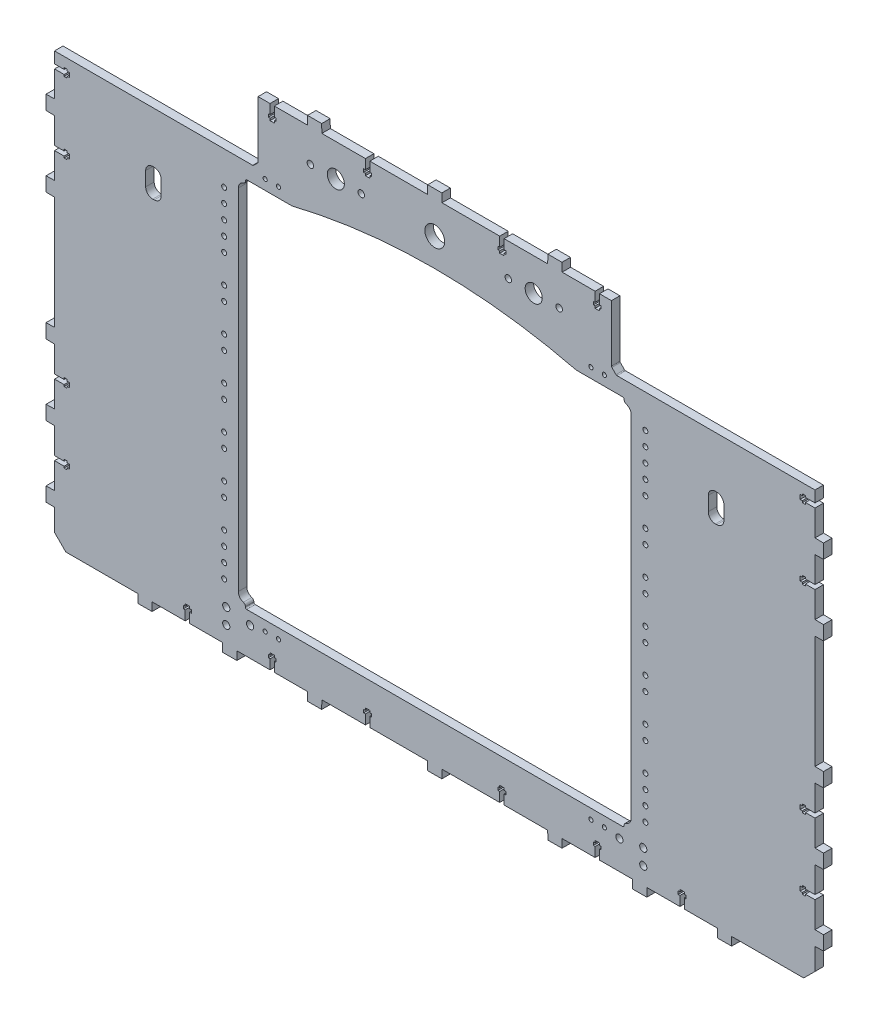
SolidWorks part; units mm, degrees
material "Клен"
ref_plane "Front" through (0, 0, 0) normal (0, 0, 1) x (1, 0, 0)
ref_plane "Top" through (0, 0, 0) normal (0, 1, 0) x (1, 0, 0)
ref_plane "Right" through (0, 0, 0) normal (1, 0, 0) x (0, 0, -1)
sketch "Эскиз1" plane through (0, 0, 0) normal (0, 0, 1) x (1, 0, 0)
  line L6 (1560.5805, 76.7865) -> (1826.5797, 76.7865)
  line L7 (1827.5797, 78.0783) -> (1827.5797, 77.7865)
  line L8 (1832.5805, 332.0072) -> (1832.5797, 84.7865)
  line L9 (1827.5805, 339.0072) -> (1827.5805, 338.7154)
  line L10 (1826.5805, 340.0072) -> (1793.6805, 340.0072)
  line L11 (1560.5805, 340.0072) -> (1592.5638, 340.0072)
  line L13 (1559.5805, 339.0072) -> (1559.5805, 338.7154)
  line L15 (1554.5805, 84.7865) -> (1554.5805, 332.0072)
  line L17 (1559.5805, 78.0783) -> (1559.5805, 77.7865)
  line L18 (1524.5805, 401.0072) -> (1524.5805, 24.1014) construction
  line L19 (1862.5805, 416.6106) -> (1862.5805, 5.7676) construction
  line L20 (1424.5805, 401.0072) -> (1424.5805, 24.1014) construction
  line L21 (1962.5805, 416.6106) -> (1962.5805, 5.7676) construction
  line L22 (1433.5805, 343.0572) -> (1435.0805, 343.0572)
  line L23 (1433.5805, 289.9572) -> (1433.5805, 288.7572)
  line L24 (1433.5805, 149.9572) -> (1433.5805, 148.7572)
  line L25 (1424.5805, 121.4072) -> (1424.5805, 103.0572)
  line L26 (1431.3805, 293.0572) -> (1431.3805, 294.2572)
  line L27 (1431.3805, 154.2572) -> (1433.5805, 154.2572)
  line L28 (1418.5805, 71.5072) -> (1424.5805, 71.4072)
  line L29 (1418.5805, 321.5072) -> (1418.5805, 311.5072)
  line L30 (1418.5805, 311.5072) -> (1424.5805, 311.4072)
  line L31 (1424.5805, 149.9572) -> (1424.5805, 131.6072)
  line L32 (1418.5805, 81.5072) -> (1418.5805, 71.5072)
  line L33 (1433.5805, 338.7572) -> (1431.3805, 338.7572)
  line L34 (1424.5805, 293.0572) -> (1431.3805, 293.0572)
  line L35 (1424.5805, 153.0572) -> (1431.3805, 153.0572)
  line L36 (1433.5805, 103.0572) -> (1435.0805, 103.0572)
  line L37 (1424.5805, 99.9572) -> (1424.5805, 81.6072)
  line L38 (1424.5805, 321.6072) -> (1418.5805, 321.5072)
  line L39 (1433.5805, 293.0572) -> (1435.0805, 293.0572)
  line L40 (1433.5805, 148.7572) -> (1431.3805, 148.7572)
  line L41 (1435.0805, 343.0572) -> (1435.0805, 339.9572)
  line L42 (1431.3805, 289.9572) -> (1424.5805, 289.9572)
  line L43 (1424.5805, 181.6072) -> (1418.5805, 181.5072)
  line L44 (1431.3805, 103.0572) -> (1431.3805, 104.2572)
  line L45 (1435.0805, 103.0572) -> (1435.0805, 99.9572)
  line L46 (1431.3805, 343.0572) -> (1431.3805, 344.2572)
  line L47 (1424.5805, 261.4072) -> (1424.5805, 181.6072)
  line L48 (1433.5805, 153.0572) -> (1435.0805, 153.0572)
  line L49 (1424.5805, 103.0572) -> (1431.3805, 103.0572)
  line L50 (1433.5805, 104.2572) -> (1433.5805, 103.0572)
  line L51 (1424.5805, 311.4072) -> (1424.5805, 293.0572)
  line L52 (1433.5805, 294.2572) -> (1433.5805, 293.0572)
  line L53 (1424.5805, 131.6072) -> (1418.5805, 131.5072)
  line L54 (1431.3805, 338.7572) -> (1431.3805, 339.9572)
  line L55 (1418.5805, 271.5072) -> (1418.5805, 261.5072)
  line L56 (1433.5805, 154.2572) -> (1433.5805, 153.0572)
  line L57 (1433.5805, 98.7572) -> (1431.3805, 98.7572)
  line L58 (1424.5805, 81.6072) -> (1418.5805, 81.5072)
  line L59 (1424.5805, 343.0572) -> (1431.3805, 343.0572)
  line L60 (1431.3805, 339.9572) -> (1424.5805, 339.9572)
  line L61 (1435.0805, 289.9572) -> (1433.5805, 289.9572)
  line L62 (1431.3805, 148.7572) -> (1431.3805, 149.9572)
  line L63 (1435.0805, 339.9572) -> (1433.5805, 339.9572)
  line L64 (1431.3805, 294.2572) -> (1433.5805, 294.2572)
  line L65 (1424.5805, 289.9572) -> (1424.5805, 271.6072)
  line L66 (1433.5805, 99.9572) -> (1433.5805, 98.7572)
  line L67 (1431.3805, 98.7572) -> (1431.3805, 99.9572)
  line L68 (1433.5805, 344.2572) -> (1433.5805, 343.0572)
  line L69 (1424.5805, 271.6072) -> (1418.5805, 271.5072)
  line L70 (1435.0805, 153.0572) -> (1435.0805, 149.9572)
  line L71 (1424.5805, 71.4072) -> (1424.5805, 56.0072)
  line L72 (1431.3805, 344.2572) -> (1433.5805, 344.2572)
  line L73 (1435.0805, 293.0572) -> (1435.0805, 289.9572)
  line L74 (1433.5805, 288.7572) -> (1431.3805, 288.7572)
  line L75 (1418.5805, 131.5072) -> (1418.5805, 121.5072)
  line L76 (1435.0805, 99.9572) -> (1433.5805, 99.9572)
  line L77 (1424.5805, 351.0072) -> (1424.5805, 343.0572)
  line L78 (1418.5805, 171.5072) -> (1424.5805, 171.4072)
  line L79 (1418.5805, 121.5072) -> (1424.5805, 121.4072)
  line L80 (1431.3805, 104.2572) -> (1433.5805, 104.2572)
  line L81 (1431.3805, 288.7572) -> (1431.3805, 289.9572)
  line L82 (1424.5805, 171.4072) -> (1424.5805, 153.0572)
  line L83 (1431.3805, 149.9572) -> (1424.5805, 149.9572)
  line L84 (1433.5805, 339.9572) -> (1433.5805, 338.7572)
  line L85 (1418.5805, 261.5072) -> (1424.5805, 261.4072)
  line L86 (1418.5805, 181.5072) -> (1418.5805, 171.5072)
  line L87 (1431.3805, 99.9572) -> (1424.5805, 99.9572)
  line L88 (1424.5805, 339.9572) -> (1424.5805, 321.6072)
  line L89 (1431.3805, 153.0572) -> (1431.3805, 154.2572)
  line L90 (1435.0805, 149.9572) -> (1433.5805, 149.9572)
  line L91 (1424.5805, 56.0072) -> (1432.5805, 48.0072)
  line L92 (1424.5805, 351.0072) -> (1524.5805, 351.0072)
  line L93 (1432.5805, 48.0072) -> (1483.4805, 48.0072)
  line L94 (1953.5805, 99.9572) -> (1952.0805, 99.9572)
  line L95 (1955.7805, 154.2572) -> (1955.7805, 153.0572)
  line L96 (1953.5805, 289.9572) -> (1952.0805, 289.9572)
  line L97 (1953.5805, 343.0572) -> (1953.5805, 344.2572)
  line L98 (1962.5805, 99.9572) -> (1955.7805, 99.9572)
  line L99 (1955.7805, 153.0572) -> (1962.5805, 153.0572)
  line L100 (1953.5805, 294.2572) -> (1955.7805, 294.2572)
  line L101 (1955.7805, 338.7572) -> (1953.5805, 338.7572)
  line L102 (1953.5805, 103.0572) -> (1953.5805, 104.2572)
  line L103 (1952.0805, 153.0572) -> (1953.5805, 153.0572)
  line L104 (1955.7805, 288.7572) -> (1953.5805, 288.7572)
  line L105 (1962.5805, 321.6072) -> (1962.5805, 339.9572)
  line L106 (1955.7805, 344.2572) -> (1955.7805, 343.0572)
  line L107 (1968.5805, 131.5072) -> (1962.5805, 131.6072)
  line L108 (1962.5805, 149.9572) -> (1955.7805, 149.9572)
  line L109 (1968.5805, 261.5072) -> (1968.5805, 271.5072)
  line L110 (1962.5805, 289.9572) -> (1955.7805, 289.9572)
  line L111 (1955.7805, 343.0572) -> (1962.5805, 343.0572)
  line L112 (1952.0805, 99.9572) -> (1952.0805, 103.0572)
  line L113 (1955.7805, 149.9572) -> (1955.7805, 148.7572)
  line L114 (1952.0805, 293.0572) -> (1953.5805, 293.0572)
  line L115 (1953.5805, 339.9572) -> (1952.0805, 339.9572)
  line L116 (1962.5805, 56.0072) -> (1962.5805, 71.4072)
  line L117 (1955.7805, 103.0572) -> (1962.5805, 103.0572)
  line L118 (1968.5805, 181.5072) -> (1962.5805, 181.6072)
  line L119 (1955.7805, 293.0572) -> (1962.5805, 293.0572)
  line L120 (1953.5805, 344.2572) -> (1955.7805, 344.2572)
  line L121 (1962.5805, 71.4072) -> (1968.5805, 71.5072)
  line L122 (1962.5805, 131.6072) -> (1962.5805, 149.9572)
  line L123 (1968.5805, 171.5072) -> (1968.5805, 181.5072)
  line L124 (1968.5805, 271.5072) -> (1962.5805, 271.6072)
  line L125 (1953.5805, 104.2572) -> (1955.7805, 104.2572)
  line L126 (1953.5805, 153.0572) -> (1953.5805, 154.2572)
  line L127 (1953.5805, 293.0572) -> (1953.5805, 294.2572)
  line L128 (1953.5805, 98.7572) -> (1953.5805, 99.9572)
  line L129 (1962.5805, 121.4072) -> (1968.5805, 121.5072)
  line L130 (1962.5805, 261.4072) -> (1968.5805, 261.5072)
  line L131 (1952.0805, 289.9572) -> (1952.0805, 293.0572)
  line L132 (1952.0805, 343.0572) -> (1953.5805, 343.0572)
  line L133 (1968.5805, 81.5072) -> (1962.5805, 81.6072)
  line L134 (1955.7805, 148.7572) -> (1953.5805, 148.7572)
  line L135 (1962.5805, 293.0572) -> (1962.5805, 311.4072)
  line L136 (1952.0805, 339.9572) -> (1952.0805, 343.0572)
  line L137 (1955.7805, 98.7572) -> (1953.5805, 98.7572)
  line L138 (1962.5805, 103.0572) -> (1962.5805, 121.4072)
  line L139 (1962.5805, 181.6072) -> (1962.5805, 261.4072)
  line L140 (1962.5805, 311.4072) -> (1968.5805, 311.5072)
  line L141 (1952.0805, 103.0572) -> (1953.5805, 103.0572)
  line L142 (1955.7805, 294.2572) -> (1955.7805, 293.0572)
  line L143 (1962.5805, 339.9572) -> (1955.7805, 339.9572)
  line L144 (1955.7805, 104.2572) -> (1955.7805, 103.0572)
  line L145 (1953.5805, 154.2572) -> (1955.7805, 154.2572)
  line L146 (1955.7805, 289.9572) -> (1955.7805, 288.7572)
  line L147 (1968.5805, 121.5072) -> (1968.5805, 131.5072)
  line L148 (1953.5805, 288.7572) -> (1953.5805, 289.9572)
  line L149 (1955.7805, 339.9572) -> (1955.7805, 338.7572)
  line L150 (1954.5805, 48.0072) -> (1962.5805, 56.0072)
  line L151 (1962.5805, 81.6072) -> (1962.5805, 99.9572)
  line L152 (1953.5805, 149.9572) -> (1952.0805, 149.9572)
  line L153 (1962.5805, 171.4072) -> (1968.5805, 171.5072)
  line L154 (1968.5805, 311.5072) -> (1968.5805, 321.5072)
  line L155 (1955.7805, 99.9572) -> (1955.7805, 98.7572)
  line L156 (1952.0805, 149.9572) -> (1952.0805, 153.0572)
  line L157 (1962.5805, 271.6072) -> (1962.5805, 289.9572)
  line L158 (1968.5805, 321.5072) -> (1962.5805, 321.6072)
  line L159 (1962.5805, 343.0572) -> (1962.5805, 351.0072)
  line L160 (1968.5805, 71.5072) -> (1968.5805, 81.5072)
  line L161 (1953.5805, 148.7572) -> (1953.5805, 149.9572)
  line L162 (1962.5805, 153.0572) -> (1962.5805, 171.4072)
  line L163 (1953.5805, 338.7572) -> (1953.5805, 339.9572)
  line L164 (1862.5805, 351.0072) -> (1962.5805, 351.0072)
  line L165 (1954.5805, 48.0072) -> (1903.6805, 48.0072)
  line L166 (1325.5433, 339.9572) -> (1983.9894, 339.9572) construction
  line L167 (1983.9894, 304.9572) -> (1788.8393, 304.9572) construction
  line L168 (1892.5805, 416.6106) -> (1892.5805, 273.8352) construction
  line L169 (1693.5805, 412.8647) -> (1693.5805, 297.5072) construction
  line L170 (1892.0805, 314.9572) -> (1893.0805, 314.9572)
  line L171 (1887.0805, 309.9572) -> (1887.0805, 299.9572)
  line L172 (1892.0805, 294.9572) -> (1893.0805, 294.9572)
  line L173 (1898.0805, 309.9572) -> (1898.0805, 299.9572)
  line L174 (1887.0805, 314.9572) -> (1898.0805, 294.9572) construction
  line L175 (1887.0805, 294.9572) -> (1898.0805, 314.9572) construction
  line L176 (1495.0805, 294.9572) -> (1494.0805, 294.9572)
  line L177 (1489.0805, 309.9572) -> (1489.0805, 299.9572)
  line L178 (1495.0805, 314.9572) -> (1494.0805, 314.9572)
  line L179 (1500.0805, 309.9572) -> (1500.0805, 299.9572)
  line L180 (1893.4805, 48.0072) -> (1893.5805, 42.0072)
  line L181 (1867.0305, 58.5072) -> (1870.1305, 58.5072)
  line L182 (1903.5805, 42.0072) -> (1903.6805, 48.0072)
  line L183 (1867.0305, 54.8072) -> (1865.8305, 54.8072)
  line L184 (1870.1305, 58.5072) -> (1870.1305, 57.0072)
  line L185 (1871.3305, 54.8072) -> (1870.1305, 54.8072)
  line L186 (1865.8305, 57.0072) -> (1867.0305, 57.0072)
  line L187 (1871.3305, 57.0072) -> (1871.3305, 54.8072)
  line L188 (1867.0305, 48.0072) -> (1867.0305, 54.8072)
  line L189 (1870.1305, 57.0072) -> (1871.3305, 57.0072)
  line L190 (1870.1305, 54.8072) -> (1870.1305, 48.0072)
  line L192 (1865.8305, 54.8072) -> (1865.8305, 57.0072)
  line L193 (1893.5805, 42.0072) -> (1903.5805, 42.0072)
  line L194 (1867.0305, 57.0072) -> (1867.0305, 58.5072)
  line L195 (1867.0305, 48.0072) -> (1854.5805, 48.0072)
  line L196 (1893.4805, 48.0072) -> (1870.1305, 48.0072)
  line L197 (1493.5805, 42.0072) -> (1493.6805, 48.0072)
  line L198 (1521.3305, 57.0072) -> (1521.3305, 54.8072)
  line L199 (1517.0305, 48.0072) -> (1517.0305, 54.8072)
  line L200 (1483.5805, 42.0072) -> (1493.5805, 42.0072)
  line L201 (1515.8305, 57.0072) -> (1517.0305, 57.0072)
  line L202 (1521.3305, 54.8072) -> (1520.1305, 54.8072)
  line L203 (1483.4805, 48.0072) -> (1483.5805, 42.0072)
  line L204 (1517.0305, 57.0072) -> (1517.0305, 58.5072)
  line L205 (1517.0305, 58.5072) -> (1520.1305, 58.5072)
  line L206 (1517.0305, 54.8072) -> (1515.8305, 54.8072)
  line L207 (1520.1305, 54.8072) -> (1520.1305, 48.0072)
  line L209 (1520.1305, 58.5072) -> (1520.1305, 57.0072)
  line L210 (1520.1305, 57.0072) -> (1521.3305, 57.0072)
  line L211 (1515.8305, 54.8072) -> (1515.8305, 57.0072)
  line L212 (1520.1305, 48.0072) -> (1532.5805, 48.0072)
  line L213 (1493.6805, 48.0072) -> (1517.0305, 48.0072)
  line L552 (1568.2876, 354.2143) -> (1565.3733, 351.3001)
  line L553 (1564.6662, 351.0072) -> (1524.5805, 351.0072)
  line L624 (1532.5805, 48.0072) -> (1543.4805, 48.0072)
  line L625 (1543.4805, 48.0072) -> (1543.5805, 42.0072)
  line L626 (1543.5805, 42.0072) -> (1553.5805, 42.0072)
  line L627 (1553.5805, 42.0072) -> (1553.6805, 48.0072)
  line L628 (1553.6805, 48.0072) -> (1577.0305, 48.0072)
  line L629 (1577.0305, 48.0072) -> (1577.0305, 54.8072)
  line L630 (1577.0305, 54.8072) -> (1575.8305, 54.8072)
  line L631 (1575.8305, 54.8072) -> (1575.8305, 57.0072)
  line L632 (1575.8305, 57.0072) -> (1577.0305, 57.0072)
  line L633 (1577.0305, 57.0072) -> (1577.0305, 58.5072)
  line L634 (1577.0305, 58.5072) -> (1580.1305, 58.5072)
  line L635 (1580.1305, 58.5072) -> (1580.1305, 57.0072)
  line L636 (1580.1305, 57.0072) -> (1581.3305, 57.0072)
  line L637 (1581.3305, 57.0072) -> (1581.3305, 54.8072)
  line L638 (1581.3305, 54.8072) -> (1580.1305, 54.8072)
  line L639 (1580.1305, 54.8072) -> (1580.1305, 48.0072)
  line L640 (1580.1305, 48.0072) -> (1603.4805, 48.0072)
  line L641 (1603.4805, 48.0072) -> (1603.5805, 42.0072)
  line L642 (1603.5805, 42.0072) -> (1613.5805, 42.0072)
  line L643 (1613.5805, 42.0072) -> (1613.6805, 48.0072)
  line L644 (1613.6805, 48.0072) -> (1644.5305, 48.0072)
  line L645 (1644.5305, 48.0072) -> (1644.5305, 54.8072)
  line L646 (1644.5305, 54.8072) -> (1643.3305, 54.8072)
  line L647 (1643.3305, 54.8072) -> (1643.3305, 57.0072)
  line L648 (1643.3305, 57.0072) -> (1644.5305, 57.0072)
  line L649 (1644.5305, 57.0072) -> (1644.5305, 58.5072)
  line L650 (1644.5305, 58.5072) -> (1647.6305, 58.5072)
  line L651 (1647.6305, 58.5072) -> (1647.6305, 57.0072)
  line L652 (1647.6305, 57.0072) -> (1648.8305, 57.0072)
  line L653 (1648.8305, 57.0072) -> (1648.8305, 54.8072)
  line L654 (1648.8305, 54.8072) -> (1647.6305, 54.8072)
  line L655 (1647.6305, 54.8072) -> (1647.6305, 48.0072)
  line L656 (1647.6305, 48.0072) -> (1688.4805, 48.0072)
  line L657 (1688.4805, 48.0072) -> (1688.5805, 42.0072)
  line L658 (1688.5805, 42.0072) -> (1698.5805, 42.0072)
  line L659 (1698.5805, 42.0072) -> (1698.6805, 48.0072)
  line L660 (1698.6805, 48.0072) -> (1739.5305, 48.0072)
  line L661 (1739.5305, 48.0072) -> (1739.5305, 54.8072)
  line L662 (1739.5305, 54.8072) -> (1738.3305, 54.8072)
  line L663 (1738.3305, 54.8072) -> (1738.3305, 57.0072)
  line L664 (1738.3305, 57.0072) -> (1739.5305, 57.0072)
  line L665 (1739.5305, 57.0072) -> (1739.5305, 58.5072)
  line L666 (1739.5305, 58.5072) -> (1742.6305, 58.5072)
  line L667 (1742.6305, 58.5072) -> (1742.6305, 57.0072)
  line L668 (1742.6305, 57.0072) -> (1743.8305, 57.0072)
  line L669 (1743.8305, 57.0072) -> (1743.8305, 54.8072)
  line L670 (1743.8305, 54.8072) -> (1742.6305, 54.8072)
  line L671 (1742.6305, 54.8072) -> (1742.6305, 48.0072)
  line L672 (1742.6305, 48.0072) -> (1773.4805, 48.0072)
  line L673 (1773.4805, 48.0072) -> (1773.5805, 42.0072)
  line L674 (1773.5805, 42.0072) -> (1783.5805, 42.0072)
  line L675 (1783.5805, 42.0072) -> (1783.6805, 48.0072)
  line L676 (1783.6805, 48.0072) -> (1807.0305, 48.0072)
  line L677 (1807.0305, 48.0072) -> (1807.0305, 54.8072)
  line L678 (1807.0305, 54.8072) -> (1805.8305, 54.8072)
  line L679 (1805.8305, 54.8072) -> (1805.8305, 57.0072)
  line L680 (1805.8305, 57.0072) -> (1807.0305, 57.0072)
  line L681 (1807.0305, 57.0072) -> (1807.0305, 58.5072)
  line L682 (1807.0305, 58.5072) -> (1810.1305, 58.5072)
  line L683 (1810.1305, 58.5072) -> (1810.1305, 57.0072)
  line L684 (1810.1305, 57.0072) -> (1811.3305, 57.0072)
  line L685 (1811.3305, 57.0072) -> (1811.3305, 54.8072)
  line L686 (1811.3305, 54.8072) -> (1810.1305, 54.8072)
  line L687 (1810.1305, 54.8072) -> (1810.1305, 48.0072)
  line L688 (1810.1305, 48.0072) -> (1833.4805, 48.0072)
  line L689 (1833.4805, 48.0072) -> (1833.5805, 42.0072)
  line L690 (1833.5805, 42.0072) -> (1843.5805, 42.0072)
  line L691 (1843.5805, 42.0072) -> (1843.6805, 48.0072)
  line L692 (1843.6805, 48.0072) -> (1854.5805, 48.0072)
  line L763 (1862.5805, 351.0072) -> (1822.4947, 351.0072)
  line L764 (1821.7876, 351.3001) -> (1818.8733, 354.2143)
  line L765 (1818.5805, 354.9215) -> (1818.5805, 395.0072)
  line L766 (1818.5805, 395.0072) -> (1810.1305, 395.0072)
  line L767 (1810.1305, 395.0072) -> (1810.1305, 388.2072)
  line L768 (1810.1305, 388.2072) -> (1811.3305, 388.2072)
  line L769 (1811.3305, 388.2072) -> (1811.3305, 386.0072)
  line L770 (1811.3305, 386.0072) -> (1810.1305, 386.0072)
  line L771 (1810.1305, 386.0072) -> (1810.1305, 384.5072)
  line L772 (1810.1305, 384.5072) -> (1807.0305, 384.5072)
  line L773 (1807.0305, 384.5072) -> (1807.0305, 386.0072)
  line L774 (1807.0305, 386.0072) -> (1805.8305, 386.0072)
  line L775 (1805.8305, 386.0072) -> (1805.8305, 388.2072)
  line L776 (1805.8305, 388.2072) -> (1807.0305, 388.2072)
  line L777 (1807.0305, 388.2072) -> (1807.0305, 395.0072)
  line L778 (1807.0305, 395.0072) -> (1783.6805, 395.0072)
  line L779 (1783.6805, 395.0072) -> (1783.5805, 401.0072)
  line L780 (1783.5805, 401.0072) -> (1773.5805, 401.0072)
  line L781 (1773.5805, 401.0072) -> (1773.4805, 395.0072)
  line L782 (1773.4805, 395.0072) -> (1742.6305, 395.0072)
  line L783 (1742.6305, 395.0072) -> (1742.6305, 388.2072)
  line L784 (1742.6305, 388.2072) -> (1743.8305, 388.2072)
  line L785 (1743.8305, 388.2072) -> (1743.8305, 386.0072)
  line L786 (1743.8305, 386.0072) -> (1742.6305, 386.0072)
  line L787 (1742.6305, 386.0072) -> (1742.6305, 384.5072)
  line L788 (1742.6305, 384.5072) -> (1739.5305, 384.5072)
  line L789 (1739.5305, 384.5072) -> (1739.5305, 386.0072)
  line L790 (1739.5305, 386.0072) -> (1738.3305, 386.0072)
  line L791 (1738.3305, 386.0072) -> (1738.3305, 388.2072)
  line L792 (1738.3305, 388.2072) -> (1739.5305, 388.2072)
  line L793 (1739.5305, 388.2072) -> (1739.5305, 395.0072)
  line L794 (1739.5305, 395.0072) -> (1698.6805, 395.0072)
  line L795 (1698.6805, 395.0072) -> (1698.5805, 401.0072)
  line L796 (1698.5805, 401.0072) -> (1688.5805, 401.0072)
  line L797 (1688.5805, 401.0072) -> (1688.4805, 395.0072)
  line L798 (1688.4805, 395.0072) -> (1647.6305, 395.0072)
  line L799 (1647.6305, 395.0072) -> (1647.6305, 388.2072)
  line L800 (1647.6305, 388.2072) -> (1648.8305, 388.2072)
  line L801 (1648.8305, 388.2072) -> (1648.8305, 386.0072)
  line L802 (1648.8305, 386.0072) -> (1647.6305, 386.0072)
  line L803 (1647.6305, 386.0072) -> (1647.6305, 384.5072)
  line L804 (1647.6305, 384.5072) -> (1644.5305, 384.5072)
  line L805 (1644.5305, 384.5072) -> (1644.5305, 386.0072)
  line L806 (1644.5305, 386.0072) -> (1643.3305, 386.0072)
  line L807 (1643.3305, 386.0072) -> (1643.3305, 388.2072)
  line L808 (1643.3305, 388.2072) -> (1644.5305, 388.2072)
  line L809 (1644.5305, 388.2072) -> (1644.5305, 395.0072)
  line L810 (1644.5305, 395.0072) -> (1613.6805, 395.0072)
  line L811 (1613.6805, 395.0072) -> (1613.5805, 401.0072)
  line L812 (1613.5805, 401.0072) -> (1603.5805, 401.0072)
  line L813 (1603.5805, 401.0072) -> (1603.4805, 395.0072)
  line L814 (1603.4805, 395.0072) -> (1580.1305, 395.0072)
  line L815 (1580.1305, 395.0072) -> (1580.1305, 388.2072)
  line L816 (1580.1305, 388.2072) -> (1581.3305, 388.2072)
  line L817 (1581.3305, 388.2072) -> (1581.3305, 386.0072)
  line L818 (1581.3305, 386.0072) -> (1580.1305, 386.0072)
  line L819 (1580.1305, 386.0072) -> (1580.1305, 384.5072)
  line L820 (1580.1305, 384.5072) -> (1577.0305, 384.5072)
  line L821 (1577.0305, 384.5072) -> (1577.0305, 386.0072)
  line L822 (1577.0305, 386.0072) -> (1575.8305, 386.0072)
  line L823 (1575.8305, 386.0072) -> (1575.8305, 388.2072)
  line L824 (1575.8305, 388.2072) -> (1577.0305, 388.2072)
  line L825 (1577.0305, 388.2072) -> (1577.0305, 395.0072)
  line L826 (1577.0305, 395.0072) -> (1568.5805, 395.0072)
  line L827 (1568.5805, 395.0072) -> (1568.5805, 354.9215)
  arc A4 (1893.0805, 294.9572) -> (1898.0805, 299.9572) centre (1893.0805, 299.9572) ccw
  arc A5 (1887.0805, 299.9572) -> (1892.0805, 294.9572) centre (1892.0805, 299.9572) ccw
  arc A6 (1893.0805, 314.9572) -> (1898.0805, 309.9572) centre (1893.0805, 309.9572) cw
  arc A7 (1892.0805, 314.9572) -> (1887.0805, 309.9572) centre (1892.0805, 309.9572) ccw
  arc A8 (1568.2876, 354.2143) -> (1568.5805, 354.9215) centre (1567.5805, 354.9215) ccw
  arc A9 (1564.6662, 351.0072) -> (1565.3733, 351.3001) centre (1564.6662, 352.0072) ccw
  arc A10 (1821.7876, 351.3001) -> (1822.4947, 351.0072) centre (1822.4947, 352.0072) ccw
  arc A11 (1818.5805, 354.9215) -> (1818.8733, 354.2143) centre (1819.5805, 354.9215) ccw
  circle A28 centre (1544.5805, 177.5072) radius 1.75
  circle A29 centre (1544.5805, 147.5072) radius 1.75
  circle A30 centre (1544.5805, 137.5072) radius 1.75
  circle A31 centre (1544.5805, 117.5072) radius 1.75
  circle A32 centre (1544.5805, 107.5072) radius 1.75
  circle A33 centre (1544.5805, 97.5072) radius 1.75
  circle A34 centre (1544.5805, 87.5072) radius 1.75
  circle A35 centre (1546.0805, 71.0072) radius 2.55
  circle A36 centre (1546.0805, 60.0072) radius 2.55
  circle A37 centre (1544.5805, 197.5072) radius 1.75
  circle A38 centre (1544.5805, 207.5072) radius 1.75
  circle A39 centre (1544.5805, 227.5072) radius 1.75
  circle A40 centre (1544.5805, 237.5072) radius 1.75
  circle A41 centre (1544.5805, 257.5072) radius 1.75
  circle A42 centre (1544.5805, 267.5072) radius 1.75
  circle A43 centre (1544.5805, 287.5072) radius 1.75
  circle A44 centre (1544.5805, 297.5072) radius 1.75
  circle A45 centre (1544.5805, 307.5072) radius 1.75
  circle A46 centre (1544.5805, 317.5072) radius 1.75
  circle A47 centre (1544.5805, 327.5072) radius 1.75
  circle A87 centre (1573.5805, 347.0072) radius 1.5
  circle A88 centre (1583.0805, 347.0072) radius 1.5
  circle A89 centre (1605.5805, 372.0072) radius 2.3
  circle A90 centre (1623.5805, 372.0072) radius 6.05
  circle A91 centre (1641.5805, 372.0072) radius 2.3
  circle A92 centre (1693.5805, 372.0072) radius 7
  circle A93 centre (1745.5805, 372.0072) radius 2.3
  circle A94 centre (1763.5805, 372.0072) radius 6.05
  circle A95 centre (1781.5805, 372.0072) radius 2.3
  circle A96 centre (1804.0805, 347.0072) radius 1.5
  circle A97 centre (1813.5805, 347.0072) radius 1.5
  circle A98 centre (1842.5805, 327.5072) radius 1.75
  circle A99 centre (1842.5805, 317.5072) radius 1.75
  circle A100 centre (1842.5805, 307.5072) radius 1.75
  circle A101 centre (1842.5805, 297.5072) radius 1.75
  circle A102 centre (1842.5805, 287.5072) radius 1.75
  circle A103 centre (1842.5805, 267.5072) radius 1.75
  circle A104 centre (1842.5805, 257.5072) radius 1.75
  circle A105 centre (1842.5805, 237.5072) radius 1.75
  circle A106 centre (1842.5805, 227.5072) radius 1.75
  circle A107 centre (1842.5805, 207.5072) radius 1.75
  circle A108 centre (1842.5805, 197.5072) radius 1.75
  circle A109 centre (1842.5805, 177.5072) radius 1.75
  circle A110 centre (1842.5805, 167.5072) radius 1.75
  circle A111 centre (1842.5805, 147.5072) radius 1.75
  circle A112 centre (1842.5805, 137.5072) radius 1.75
  circle A113 centre (1842.5805, 117.5072) radius 1.75
  circle A114 centre (1842.5805, 107.5072) radius 1.75
  circle A115 centre (1842.5805, 97.5072) radius 1.75
  circle A116 centre (1842.5805, 87.5072) radius 1.75
  circle A117 centre (1841.0805, 71.0072) radius 2.55
  circle A118 centre (1841.0805, 60.0072) radius 2.55
  circle A119 centre (1824.2277, 68.2968) radius 2.55
  circle A120 centre (1813.5805, 69.7865) radius 1.5
  circle A121 centre (1804.0805, 69.7865) radius 1.5
  circle A122 centre (1583.0805, 69.7865) radius 1.5
  circle A123 centre (1573.5805, 69.7865) radius 1.5
  circle A124 centre (1562.9305, 68.2968) radius 2.55
  circle A125 centre (1544.5805, 167.5072) radius 1.75
  arc A133 (1826.5797, 76.7865) -> (1827.5797, 77.7865) centre (1826.5797, 77.7865) ccw
  arc A134 (1829.0083, 79.995) -> (1827.5797, 78.0783) centre (1829.5797, 78.0783) ccw
  arc A135 (1829.0083, 79.995) -> (1832.5797, 84.7865) centre (1827.5797, 84.7865) ccw
  arc A136 (1832.5805, 332.0072) -> (1829.009, 336.7988) centre (1827.5805, 332.0072) ccw
  arc A137 (1827.5805, 338.7154) -> (1829.009, 336.7988) centre (1829.5805, 338.7154) ccw
  arc A138 (1827.5805, 339.0072) -> (1826.5805, 340.0072) centre (1826.5805, 339.0072) ccw
  arc A139 (1793.6805, 340.0072) -> (1592.5638, 340.0072) centre (1693.1221, -70.0562) ccw
  arc A141 (1560.5805, 340.0072) -> (1559.5805, 339.0072) centre (1560.5805, 339.0072) ccw
  arc A143 (1558.1519, 336.7988) -> (1559.5805, 338.7154) centre (1557.5805, 338.7154) ccw
  arc A145 (1558.1519, 336.7988) -> (1554.5805, 332.0072) centre (1559.5805, 332.0072) ccw
  arc A147 (1559.5805, 77.7865) -> (1560.5805, 76.7865) centre (1560.5805, 77.7865) ccw
  arc A149 (1554.5805, 84.7865) -> (1558.1519, 79.995) centre (1559.5805, 84.7865) ccw
  arc A151 (1559.5805, 78.0783) -> (1558.1519, 79.995) centre (1557.5805, 78.0783) ccw
  arc A152 (1494.0805, 294.9572) -> (1489.0805, 299.9572) centre (1494.0805, 299.9572) cw
  arc A153 (1494.0805, 314.9572) -> (1489.0805, 309.9572) centre (1494.0805, 309.9572) ccw
  arc A154 (1500.0805, 299.9572) -> (1495.0805, 294.9572) centre (1495.0805, 299.9572) cw
  arc A155 (1495.0805, 314.9572) -> (1500.0805, 309.9572) centre (1495.0805, 309.9572) cw
  point P18 (1892.5805, 304.9572)
  dimension "D7" = 5
  dimension "D2" = 100
  dimension "D3" = 100
  dimension "D4" = 30
  dimension "D1" = 35
  dimension "D5" = 11
  dimension "D6" = 20
extrude "Бобышка-Вытянуть1" add sketch "Эскиз1" along normal blind 6
